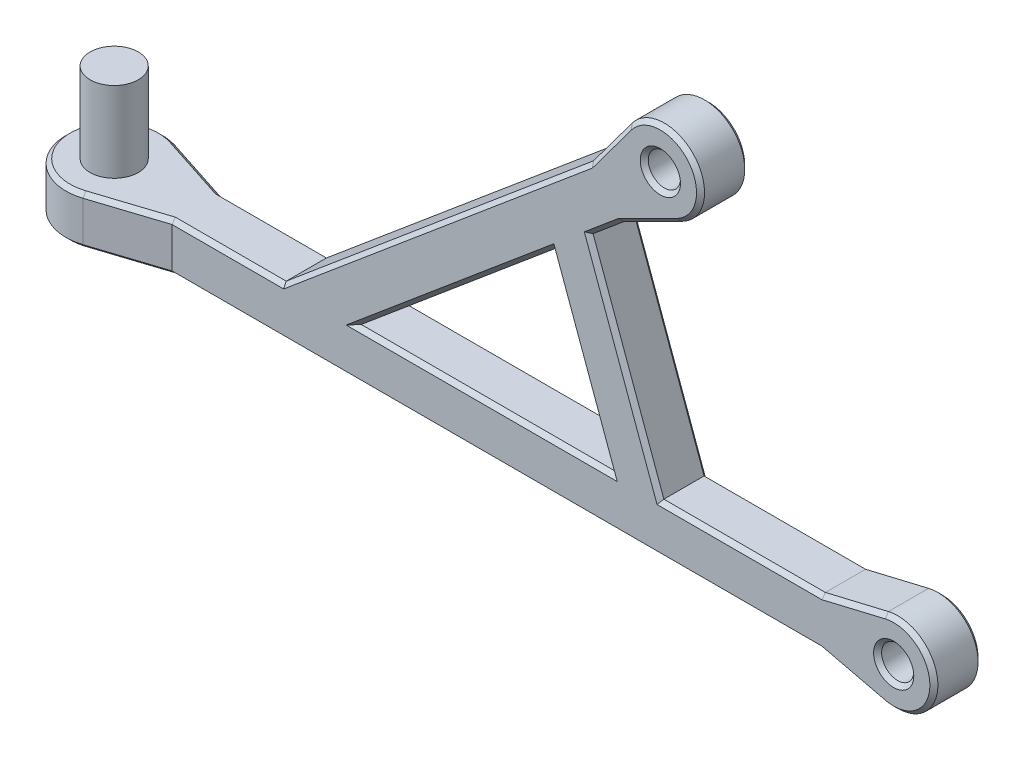
SolidWorks part; units mm, degrees
ref_plane "前视基准面" through (0, 0, 0) normal (0, 0, 1) x (1, 0, 0)
ref_plane "上视基准面" through (0, 0, 0) normal (0, 1, 0) x (1, 0, 0)
ref_plane "右视基准面" through (0, 0, 0) normal (1, 0, 0) x (0, 0, -1)
other "Configuration Table"
sketch "草图1" plane through (0, 0, 0) normal (0, 1, 0) x (1, 0, 0)
  circle A0 centre (0, 0) radius 1.5
  dimension "D1" = 3
extrude "凸台-拉伸1" add sketch "草图1" along normal blind 5
sketch "草图2" plane through (0, 0, 0) normal (0, 1, 0) x (1, 0, 0)
  line L0 (0, 0) -> (50, 0) construction
  line L1 (50, 1.5) -> (50, -1.5)
  line L2 (50, 1.5) -> (2.5981, 1.5)
  line L3 (50, -1.5) -> (2.5981, -1.5)
  arc A0 (2.5981, 1.5) -> (2.5981, -1.5) centre (0, 0) ccw
  point P9 (50, 0)
  dimension "D1" = 6
  dimension "D2" = 50
  dimension "D3" = 3
extrude "凸台-拉伸2" add sketch "草图2" against normal blind 3
sketch "草图3" plane through (0, 0, 0) normal (0, 0, 1) x (1, 0, 0)
  line L0 (50, -3) -> (50, 0) construction
  circle A0 centre (50, -1.5) radius 2.5
  dimension "D1" = 5
extrude "凸台-拉伸3" add sketch "草图3" along normal up to surface (3 mm away) from surface at -1.5 up to face at (26.299, -1.5, 1.5) starting at face at (26.299, -1.5, -1.5)
sketch "草图4" plane through (0, 0, 0) normal (0, 0, 1) x (1, 0, 0)
  circle A0 centre (50, -1.5) radius 1
  dimension "D1" = 2
extrude "切除-拉伸1" cut sketch "草图4" along normal up to surface (3 mm away) from surface at -1.5 up to face at (26.424, -1.5, 1.5) starting at face at (26.424, -1.5, -1.5)
sketch "草图5" plane through (0, 0, 0) normal (0, 1, 0) x (1, 0, 0)
  line L0 (5.0981, 1.5) -> (0.9258, 2.8536)
  line L1 (5.0981, -1.5) -> (0.9258, -2.8536)
  line L3 (48, -1.5) -> (48, 1.5)
  line L4 (48, 1.5) -> (2.5981, 1.5)
  line L5 (2.5981, -1.5) -> (48, -1.5)
  line L7 (5.0981, 1.5) -> (2.5981, 1.5)
  line L8 (2.5981, -1.5) -> (5.0981, -1.5)
  arc A0 (0.9258, -2.8536) -> (2.5981, -1.5) centre (0, 0) ccw
  arc A1 (2.5981, 1.5) -> (2.5981, -1.5) centre (0, 0) ccw
  arc A2 (2.5981, 1.5) -> (0.9258, 2.8536) centre (0, 0) ccw
  dimension "D2" = 2.5
  dimension "D3" = 2.5
  dimension "D1" = 0
extrude "凸台-拉伸4" add sketch "草图5" against normal up to surface (3 mm away) up to face at (23.8995, -3, 0)
sketch "草图6" plane through (0, 0, 0) normal (0, 0, 1) x (1, 0, 0)
  line L0 (45.5, 0) -> (49.4219, 0.9322)
  line L1 (45.5, -3) -> (49.4219, -3.9322)
  line L3 (5.0981, 0) -> (5.0981, -3)
  line L4 (5.0981, -3) -> (48, -3)
  line L5 (48, 0) -> (5.0981, 0)
  line L7 (45.5, -3) -> (48, -3)
  line L8 (48, 0) -> (45.5, 0)
  arc A0 (49.4219, 0.9322) -> (48, 0) centre (50, -1.5) ccw
  arc A1 (48, -3) -> (48, 0) centre (50, -1.5) ccw
  arc A2 (48, -3) -> (49.4219, -3.9322) centre (50, -1.5) ccw
  dimension "D2" = 2.5
  dimension "D3" = 2.5
  dimension "D1" = 0
extrude "凸台-拉伸5" add sketch "草图6" along normal up to surface (3 mm away) from surface at -1.5 up to face at (27.674, -1.5, 1.5) starting at face at (27.674, -1.5, -1.5)
sketch "草图9" plane through (0, 0, 0) normal (0, 0, 1) x (1, 0, 0)
  line L0 (-989.01, -1.5) -> (49010.99, -1.5) construction
  line L1 (12.5, -1.5) -> (35.4813, 17.7836) construction
  line L2 (16.6212, 0) -> (34.9134, 15.349)
  line L3 (11.954, 0) -> (32.9851, 17.6471)
  line L4 (5.0981, 0) -> (45.5, 0) construction
  line L5 (11.954, 0) -> (16.6212, 0)
  arc A0 (34.9134, 15.349) -> (32.9851, 17.6471) centre (35.4813, 17.7836) ccw
  circle A1 centre (35.4813, 17.7836) radius 1
  dimension "D5" = 5
  dimension "D7" = 2
  dimension "D1" = 1.5
  dimension "D2" = 40
  dimension "D3" = 12.5
  dimension "D4" = 30
  dimension "D6" = 3
extrude "凸台-拉伸6" add sketch "草图9" along normal up to surface (3 mm away) from surface at -1.5 up to face at (33.853, -1.5, 1.5) starting at face at (33.853, -1.5, -1.5)
sketch "草图10" plane through (0, 0, 0) normal (0, 0, 1) x (1, 0, 0)
  line L0 (32.9983, 13.742) -> (36.6019, 15.5488)
  line L1 (31.07, 16.0402) -> (33.475, 19.2752)
  line L8 (49.4219, 0.9322) -> (45.5, 0)
  line L9 (45.5, 0) -> (16.6212, 0)
  line L10 (16.6212, 0) -> (34.9134, 15.349)
  line L11 (32.9851, 17.6471) -> (11.954, 0)
  line L12 (11.954, 0) -> (5.0981, 0)
  line L13 (5.0981, 0) -> (5.0981, -3)
  line L14 (5.0981, -3) -> (45.5, -3)
  line L15 (45.5, -3) -> (49.4219, -3.9322)
  line L18 (32.9983, 13.742) -> (34.9134, 15.349)
  line L19 (32.9851, 17.6471) -> (31.07, 16.0402)
  arc A0 (33.475, 19.2752) -> (32.9851, 17.6471) centre (35.4813, 17.7836) ccw
  arc A2 (34.9134, 15.349) -> (32.9851, 17.6471) centre (35.4813, 17.7836) ccw
  arc A3 (49.4219, -3.9322) -> (49.4219, 0.9322) centre (50, -1.5) ccw
  arc A4 (34.9134, 15.349) -> (36.6019, 15.5488) centre (35.4813, 17.7836) ccw
  dimension "D2" = 2.5
  dimension "D3" = 2.5
  dimension "D1" = 0
extrude "凸台-拉伸7" add sketch "草图10" along normal up to surface (3 mm away) from surface at -1.5 up to face at (30.3039, 2.6889, 1.5) starting at face at (30.3039, 2.6889, -1.5)
sketch "草图11" plane through (0, 0, 0) normal (0, 0, 1) x (1, 0, 0)
  line L0 (-1000.0493, -1.5) -> (48999.9507, -1.5) construction
  line L1 (31.0457, 12.1036) -> (35.451, 0)
  line L2 (32.9983, 13.742) -> (16.6212, 0) construction
  line L3 (16.6212, 0) -> (45.5, 0) construction
  line L4 (35.451, 0) -> (32.4437, 0)
  line L5 (32.4437, 0) -> (28.7419, 10.1705)
  line L6 (28.7419, 10.1705) -> (31.0457, 12.1036)
  circle A0 centre (12.5, -1.5) radius 20 construction
  circle A1 centre (12.5, -1.5) radius 23 construction
  dimension "D3" = 40
  dimension "D4" = 46
  dimension "D1" = 1.5
  dimension "D2" = 12.5
extrude "凸台-拉伸8" add sketch "草图11" against normal up to surface (3 mm away) from surface at 1.5 up to face at (30.683, 4.7987, -1.5) starting at face at (30.683, 4.7987, 1.5)
chamfer "倒角5" distance 0.25 angle 45 33 edges at (37.3964, 19.3906, 1.5) (32.2725, 17.6577, -1.5) (32.2725, 17.6577, 1.5) (22.6816, 5.0852, 1.5) (22.6816, 5.0852, -1.5) (40.4755, 0, 1.5) (24.5324, 0, -1.5) (30.5928, 5.0852, 1.5) (33.2484, 6.0518, 1.5) (30.5928, 5.0852, -1.5) (33.2484, 6.0518, -1.5) (49, -1.5, -1.5) (51, -1.5, 1.5) (8.5261, 0, 1.5) (25.299, -3, 1.5) (25.299, -3, -1.5) (47.4609, -3.4661, -1.5) (47.4609, -3.4661, 1.5) (52.5, -1.5, -1.5) (52.5, -1.5, 1.5) (40.4755, 0, -1.5) (47.4609, 0.4661, -1.5) (47.4609, 0.4661, 1.5) (8.5261, 0, -1.5) (24.5324, 0, 1.5) (21.512, 8.0201, 1.5) (21.512, 8.0201, -1.5) (36.4813, 17.7836, 1.5) (32.022, 12.9228, 1.5) (32.022, 12.9228, -1.5) (34.8001, 14.6454, -1.5) (34.8001, 14.6454, 1.5) (37.3964, 19.3906, -1.5)
chamfer "倒角6" distance 0.25 angle 45 6 edges at (3.3972, 0, -2.0518) (3.3972, 0, 2.0518) (-3, 0, 0) (3.3972, -3, -2.0518) (3.3972, -3, 2.0518) (-3, -3, 0)
